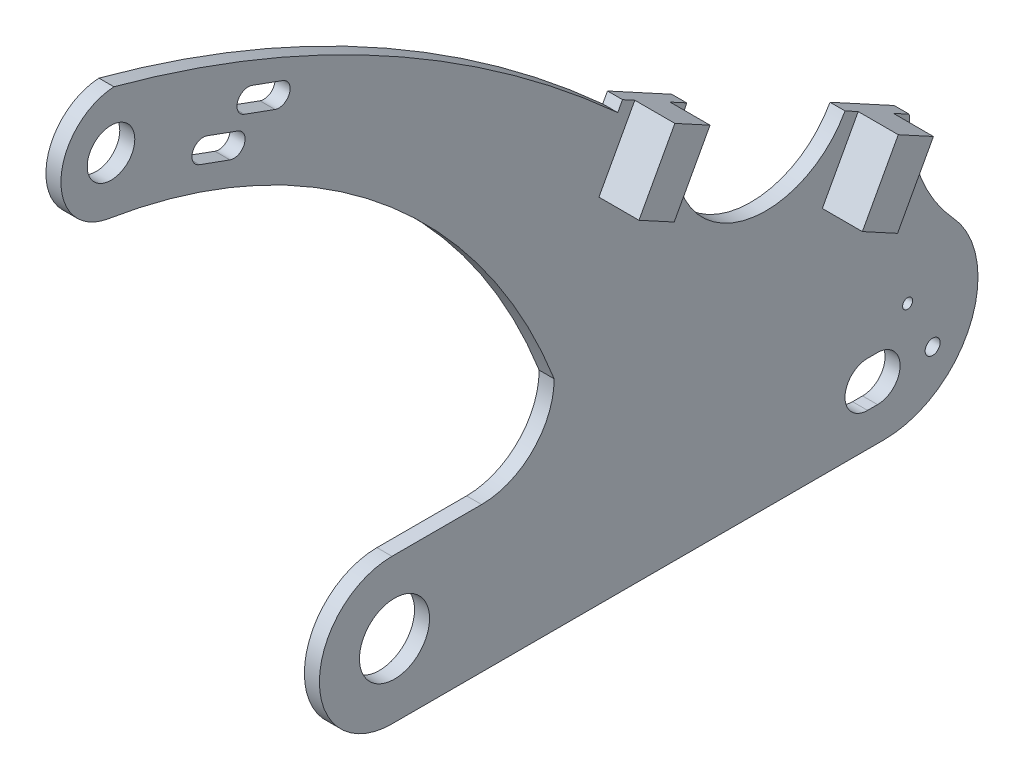
SolidWorks part; units mm, degrees
material "AISI 1020"
ref_plane "Front Plane" through (0, 0, 0) normal (0, 0, 1) x (1, 0, 0)
ref_plane "Top Plane" through (0, 0, 0) normal (0, 1, 0) x (1, 0, 0)
ref_plane "Right Plane" through (0, 0, 0) normal (1, 0, 0) x (0, 0, -1)
sketch "Sketch1" plane through (0, 0, 0) normal (1, 0, 0) x (0, 0, -1)
  line L0 (-49.1593, 0) -> (49.1593, 0)
  line L1 (49.1593, 37.5) -> (41.1593, 37.5) construction
  line L2 (-49.1593, 29) -> (-31.2593, 29)
  line L3 (0, -31.4761) -> (0, 31.4761) construction
  line L4 (-104.7059, 138) -> (-37.7059, 138) construction
  line L5 (32.1487, 42.1907) -> (-34.9377, 138) construction
  line L6 (45.8407, 11.2423) -> (47.8407, 11.2423) construction
  line L7 (45.8407, 15.7423) -> (47.8407, 15.7423)
  line L8 (45.8407, 6.7423) -> (47.8407, 6.7423)
  line L9 (-104.7059, 138) -> (-105.873, 115.7306) construction
  line L10 (-105.2895, 126.8653) -> (-115.2758, 127.3886) construction
  line L11 (-16.7593, 43.5) -> (-24.2593, 56.4904) construction
  line L12 (59.6251, 11.2423) -> (61.3276, 11.2423) construction
  line L13 (-49.478, 14.5) -> (-46.5284, 14.5) construction
  line L14 (-48.29, 14.5) -> (-46.0777, 14.5) construction
  line L15 (-86.8655, 118.0957) -> (-80.7575, 115.8726) construction
  line L16 (-86.096, 120.21) -> (-79.988, 117.9869)
  line L17 (-87.6351, 115.9814) -> (-81.5271, 113.7583)
  line L18 (-87.841, 113.2563) -> (-77.7033, 113.2563) construction
  line L19 (-77.8737, 122.3244) -> (-71.7657, 120.1012) construction
  line L20 (-77.1041, 124.4387) -> (-70.9961, 122.2155)
  line L21 (-78.6432, 120.21) -> (-72.5352, 117.9869)
  line L22 (-80.7575, 117.9869) -> (-78.616, 117.9869) construction
  line L23 (-72.7481, 117.9869) -> (-70.635, 117.9869) construction
  line L24 (41.3407, 60.8) -> (9.7153, 78) construction
  line L25 (9.7153, 78) -> (-3.1105, 84.9756)
  line L26 (41.3407, 60.8) -> (54.1665, 53.8244)
  line L28 (-3.1105, 84.9756) -> (-4.066, 83.2186)
  arc A3 (-49.1593, 0) -> (-49.1593, 29) centre (-49.1593, 14.5) cw
  arc A4 (62.9185, 31.4877) -> (49.1593, 0) centre (49.1593, 18.75) cw
  arc A5 (41.1593, 37.5) -> (32.1487, 42.1907) centre (41.1593, 48.5) cw construction
  arc A6 (32.1487, 42.1907) -> (25.3729, 51.4007) centre (-167.8609, -97.8576) ccw construction
  arc A7 (-16.7593, 43.5) -> (-31.2593, 29) centre (-31.2593, 43.5) cw
  arc A12 (-104.7059, 138) -> (-105.873, 115.7306) centre (-104.075, 126.8016) ccw
  arc A13 (-105.873, 115.7306) -> (-16.7593, 43.5) centre (-124.3727, 1.8199) cw
  circle A14 centre (58.8407, 11.2423) radius 1.5
  arc A15 (45.8407, 15.7423) -> (45.8407, 6.7423) centre (45.8407, 11.2423) ccw
  arc A16 (47.8407, 6.7423) -> (47.8407, 15.7423) centre (47.8407, 11.2423) ccw
  circle A17 centre (53.8407, 21.2423) radius 1
  circle A18 centre (-48.6593, 14.5) radius 7
  circle A19 centre (-105.2895, 126.8653) radius 4.75
  arc A20 (-86.096, 120.21) -> (-87.6351, 115.9814) centre (-86.8655, 118.0957) ccw
  arc A21 (-81.5271, 113.7583) -> (-79.988, 117.9869) centre (-80.7575, 115.8726) ccw
  arc A22 (-77.1041, 124.4387) -> (-78.6432, 120.21) centre (-77.8737, 122.3244) ccw
  arc A23 (-72.5352, 117.9869) -> (-70.9961, 122.2155) centre (-71.7657, 120.1012) ccw
  arc A24 (9.7153, 78) -> (41.3407, 60.8) centre (25.528, 69.4) ccw
  arc A25 (54.1665, 53.8244) -> (62.9185, 31.4877) centre (87.0463, 53.8244) ccw
  arc A26 (-4.066, 83.2186) -> (-104.7059, 138) centre (-167.8609, -97.8576) ccw
  point P2 (-63.6593, 14.5)
  point P3 (66.3407, 11.2423)
  point P5 (0, 0)
  point P14 (0, 0)
  point P26 (46.8407, 11.2423)
  point P34 (-115.2758, 127.3886)
  point P39 (41.3407, 11.2423)
  point P40 (52.3407, 11.2423)
  point P53 (-83.8115, 116.9842)
  point P60 (-88.9799, 118.8653)
  point P61 (-78.6432, 115.1031)
  point P64 (-74.8197, 121.2128)
  point P71 (-79.988, 123.0939)
  point P72 (-69.6514, 119.3317)
  point P77 (-75.5892, 119.0985)
  dimension "D4" = 11
  dimension "D3" = 14.5
  dimension "D1" = 130
  dimension "D2" = 18.75
  dimension "D8" = 14.5
  dimension "D15" = 22.3
  dimension "D17" = 93
  dimension "D18" = 15
  dimension "D11" = 3
  dimension "D16" = 11
  dimension "D21" = 2
  dimension "D24" = 14
  dimension "D26" = 9.5
  dimension "D34" = 36
  dimension "D5" = 8
  dimension "D6" = 125
  dimension "D7" = 138
  dimension "D9" = 67
  dimension "D10" = 32.4
  dimension "D12" = 10
  dimension "D13" = 7.5
  dimension "D14" = 14.5
  dimension "D19" = 9
  dimension "D20" = 14
  dimension "D22" = 12.5
  dimension "D23" = 10
  dimension "D25" = 15
  dimension "D27" = 11
  dimension "D28" = 4.5
  dimension "D29" = 20
  dimension "D30" = 16.3096
  dimension "D31" = 8
  dimension "D32" = 11
  dimension "D33" = 4.5
  dimension "D35" = 60.8
  dimension "D36" = 78
  dimension "D37" = 14.6
  dimension "D38" = 2
extrude "Boss-Extrude1" add sketch "Sketch1" along normal blind 3
sketch "Sketch2" plane through (3, 0, 0) normal (1, 0, 0) x (0, 0, -1)
  line L0 (54.1665, 53.8244) -> (41.3407, 60.8) construction
  line L1 (43.9761, 59.3667) -> (51.0039, 55.5444)
  line L2 (43.9761, 59.3667) -> (36.8094, 46.1895)
  line L3 (36.8094, 46.1895) -> (43.8373, 42.3672)
  line L4 (51.0039, 55.5444) -> (43.8373, 42.3672)
  line L5 (9.7153, 78) -> (-3.1105, 84.9756) construction
  line L6 (-0.6507, 83.6378) -> (6.3771, 79.8156)
  line L7 (-0.6507, 83.6378) -> (-7.8174, 70.4606)
  line L8 (-7.8174, 70.4606) -> (-0.7895, 66.6383)
  line L9 (6.3771, 79.8156) -> (-0.7895, 66.6383)
  arc A0 (9.7153, 78) -> (41.3407, 60.8) centre (25.528, 69.4) ccw construction
  arc A1 (9.7153, 78) -> (41.3407, 60.8) centre (25.528, 69.4) ccw construction
  dimension "D1" = 8
  dimension "D2" = 15
  dimension "D3" = 3
  dimension "D4" = 3.8
extrude "Boss-Extrude2" add sketch "Sketch2" along normal blind 8
